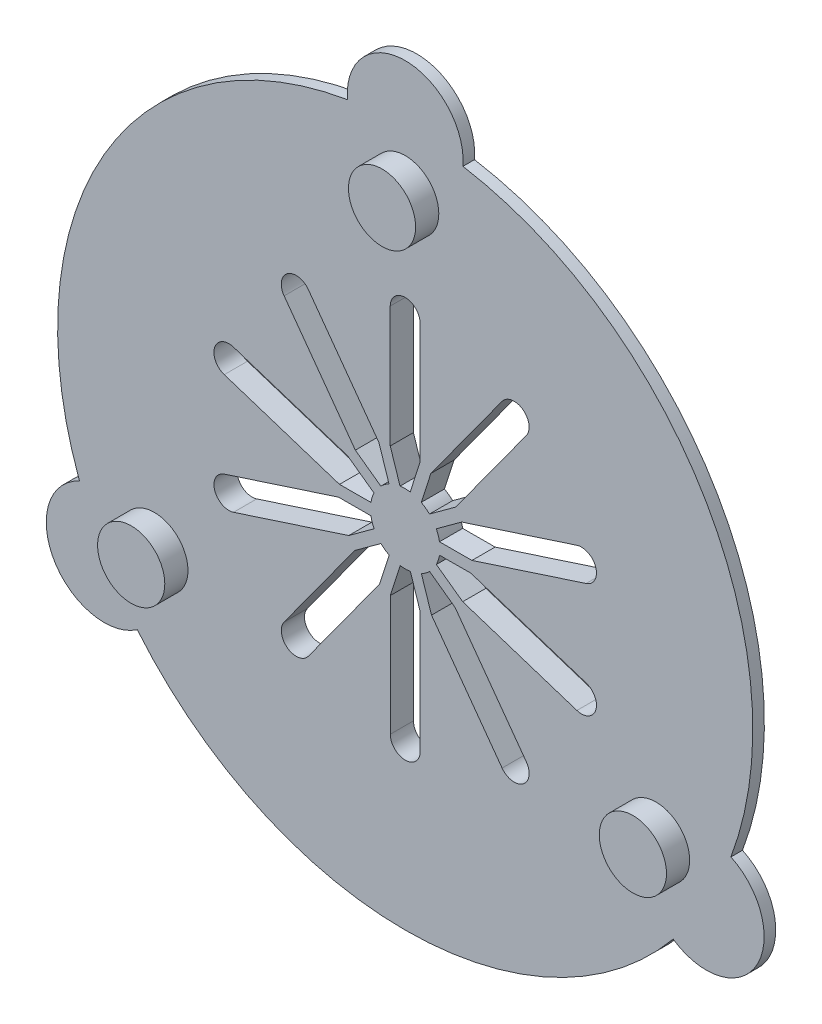
SolidWorks part; units mm, degrees
ref_plane "Спереди" through (0, 0, 0) normal (0, 0, 1) x (1, 0, 0)
ref_plane "Сверху" through (0, 0, 0) normal (0, 1, 0) x (1, 0, 0)
ref_plane "Справа" through (0, 0, 0) normal (1, 0, 0) x (0, 0, -1)
sketch "Sketch1" plane through (0, 0, 0) normal (0, 0, 1) x (1, 0, 0)
  line L0 (3.9, 6.755) -> (7.8, 0) construction
  line L2 (5.85, 10.1325) -> (11.7, 0) construction
  line L4 (7.8, 13.51) -> (15.6, 0) construction
  circle A61 centre (0, 0) radius 20
  circle A131 centre (0, 0) radius 1.25
  circle A484 centre (3.9, 0) radius 1.25
  circle A485 centre (7.8, 0) radius 1.25
  circle A486 centre (11.7, 0) radius 1.25
  circle A487 centre (15.6, 0) radius 1.25
  circle A488 centre (1.95, -3.3775) radius 1.25
  circle A489 centre (3.9, -6.755) radius 1.25
  circle A490 centre (5.85, -10.1325) radius 1.25
  circle A491 centre (7.8, -13.51) radius 1.25
  circle A492 centre (-1.95, -3.3775) radius 1.25
  circle A493 centre (-3.9, -6.755) radius 1.25
  circle A494 centre (-5.85, -10.1325) radius 1.25
  circle A495 centre (-7.8, -13.51) radius 1.25
  circle A496 centre (-3.9, 0) radius 1.25
  circle A497 centre (-7.8, 0) radius 1.25
  circle A498 centre (-11.7, 0) radius 1.25
  circle A499 centre (-15.6, 0) radius 1.25
  circle A500 centre (-1.95, 3.3775) radius 1.25
  circle A501 centre (-3.9, 6.755) radius 1.25
  circle A502 centre (-5.85, 10.1325) radius 1.25
  circle A503 centre (-7.8, 13.51) radius 1.25
  circle A504 centre (1.95, 3.3775) radius 1.25
  circle A505 centre (3.9, 6.755) radius 1.25
  circle A506 centre (5.85, 10.1325) radius 1.25
  circle A507 centre (7.8, 13.51) radius 1.25
  circle A508 centre (5.85, 3.3775) radius 1.25
  circle A509 centre (7.8, 6.755) radius 1.25
  circle A510 centre (9.75, 3.3775) radius 1.25
  circle A511 centre (11.7, 6.755) radius 1.25
  circle A512 centre (9.7491, 10.1341) radius 1.25
  circle A513 centre (13.6509, 3.3759) radius 1.25
  circle A514 centre (5.85, -3.3791) radius 1.25
  circle A515 centre (9.75, -3.3791) radius 1.25
  circle A516 centre (7.8, -6.7566) radius 1.25
  circle A517 centre (11.7, -6.7566) radius 1.25
  circle A518 centre (9.7491, -10.1356) radius 1.25
  circle A519 centre (13.6509, -3.3775) radius 1.25
  circle A520 centre (-0.0013, -6.7573) radius 1.25
  circle A521 centre (1.9487, -10.1348) radius 1.25
  circle A522 centre (-1.9513, -10.1348) radius 1.25
  circle A523 centre (-0.0013, -13.5123) radius 1.25
  circle A524 centre (-3.9032, -13.5123) radius 1.25
  circle A525 centre (3.9005, -13.5123) radius 1.25
  circle A526 centre (-5.8527, -3.3791) radius 1.25
  circle A527 centre (-7.8027, -6.7566) radius 1.25
  circle A528 centre (-9.7527, -3.3791) radius 1.25
  circle A529 centre (-11.7027, -6.7566) radius 1.25
  circle A530 centre (-13.6536, -3.3775) radius 1.25
  circle A531 centre (-9.7518, -10.1356) radius 1.25
  circle A532 centre (-5.8527, 3.3775) radius 1.25
  circle A533 centre (-9.7527, 3.3775) radius 1.25
  circle A534 centre (-7.8027, 6.755) radius 1.25
  circle A535 centre (-11.7027, 6.755) radius 1.25
  circle A536 centre (-9.7518, 10.1341) radius 1.25
  circle A537 centre (-13.6536, 3.3759) radius 1.25
  circle A538 centre (-0.0014, 6.7558) radius 1.25
  circle A539 centre (-1.9514, 10.1333) radius 1.25
  circle A540 centre (1.9486, 10.1333) radius 1.25
  circle A541 centre (-0.0014, 13.5108) radius 1.25
  circle A542 centre (3.9005, 13.5108) radius 1.25
  circle A543 centre (-3.9032, 13.5108) radius 1.25
  circle A544 centre (13.65, -1.1258) radius 2.2517 construction
  circle A545 centre (11.7009, -4.5044) radius 2.2522 construction
  circle A546 centre (9.75, -7.8834) radius 2.2522 construction
  circle A547 centre (7.7987, -11.2591) radius 2.2509 construction
  circle A548 centre (13.65, -1.1258) radius 0.65
  circle A549 centre (11.7009, -4.5044) radius 0.65
  circle A550 centre (9.75, -7.8834) radius 0.65
  circle A551 centre (7.7987, -11.2591) radius 0.65
  circle A552 centre (9.75, -1.1258) radius 0.65
  circle A553 centre (7.8009, -4.5044) radius 0.65
  circle A554 centre (5.85, -7.8834) radius 0.65
  circle A555 centre (3.8987, -11.2591) radius 0.65
  circle A556 centre (5.85, -1.1258) radius 0.65
  circle A557 centre (3.9009, -4.5044) radius 0.65
  circle A558 centre (1.95, -7.8834) radius 0.65
  circle A559 centre (-0.0013, -11.2591) radius 0.65
  circle A560 centre (1.95, -1.1258) radius 0.65
  circle A561 centre (0.0009, -4.5044) radius 0.65
  circle A562 centre (-1.95, -7.8834) radius 0.65
  circle A563 centre (-3.9013, -11.2591) radius 0.65
  circle A564 centre (-1.95, -1.1258) radius 0.65
  circle A565 centre (-3.8991, -4.5044) radius 0.65
  circle A566 centre (-5.85, -7.8834) radius 0.65
  circle A567 centre (-7.8013, -11.2591) radius 0.65
  circle A568 centre (-5.85, -1.1258) radius 0.65
  circle A569 centre (-7.7991, -4.5044) radius 0.65
  circle A570 centre (-9.75, -7.8834) radius 0.65
  circle A572 centre (-9.75, -1.1258) radius 0.65
  circle A573 centre (-11.6991, -4.5044) radius 0.65
  circle A576 centre (-13.65, -1.1258) radius 0.65
  circle A587 centre (0, 2.2517) radius 2.2517 construction
  circle A588 centre (0, 2.2517) radius 0.65
  circle A589 centre (3.9, 2.2517) radius 0.65
  circle A590 centre (7.8, 2.2517) radius 0.65
  circle A591 centre (11.7, 2.2517) radius 0.65
  circle A592 centre (15.6, 2.2517) radius 0.65
  circle A593 centre (1.9491, 5.6297) radius 2.2522 construction
  circle A594 centre (1.9491, 5.6297) radius 0.65
  circle A595 centre (5.8491, 5.6297) radius 0.65
  circle A596 centre (9.7491, 5.6297) radius 0.65
  circle A597 centre (13.6491, 5.6297) radius 0.65
  circle A598 centre (3.8991, 9.0072) radius 2.2522 construction
  circle A599 centre (3.8991, 9.0072) radius 0.65
  circle A600 centre (7.7991, 9.0072) radius 0.65
  circle A601 centre (11.6991, 9.0072) radius 0.65
  circle A602 centre (5.85, 12.3842) radius 2.2517 construction
  circle A603 centre (5.85, 12.3842) radius 0.65
  circle A604 centre (9.75, 12.3842) radius 0.65
  circle A605 centre (5.85, -14.6358) radius 0.65
  circle A606 centre (1.9509, -14.6353) radius 0.65
  circle A607 centre (-1.9491, -14.6353) radius 0.65
  circle A608 centre (-5.85, -14.6358) radius 0.65
  circle A609 centre (-15.6, 2.2517) radius 0.65
  circle A610 centre (-13.65, 5.6281) radius 0.65
  circle A611 centre (-11.7, 9.0056) radius 0.65
  circle A612 centre (-9.75, 12.3842) radius 0.65
  circle A613 centre (-5.85, 12.3842) radius 0.65
  circle A614 centre (-1.95, 12.3842) radius 0.65
  circle A615 centre (1.95, 12.3842) radius 0.65
  circle A616 centre (-7.8, 9.0056) radius 0.65
  circle A617 centre (-9.75, 5.6281) radius 0.65
  circle A618 centre (-11.7, 2.2517) radius 0.65
  circle A619 centre (-3.9, 9.0056) radius 0.65
  circle A620 centre (-5.85, 5.6281) radius 0.65
  circle A621 centre (-7.8, 2.2517) radius 0.65
  circle A622 centre (0, 9.0056) radius 0.65
  circle A623 centre (-1.95, 5.6281) radius 0.65
  circle A624 centre (-3.9, 2.2517) radius 0.65
  circle A625 centre (-15.5991, -4.5044) radius 0.65
  circle A626 centre (-13.65, -7.8834) radius 0.65
  circle A627 centre (-17.55, -7.8834) radius 0.65
  circle A628 centre (-19.5013, -11.2591) radius 0.65
  circle A629 centre (-15.6013, -11.2591) radius 0.65
  circle A630 centre (-11.7013, -11.2591) radius 0.65
  point P51 (0, 0)
  point P125 (-0.0013, -0.0008)
  point P231 (0, 0)
  dimension "D1" = 5
  dimension "D3" = 6
  dimension "D5" = 8
  dimension "D7" = 4
  dimension "D11" = 4
  dimension "D2" = 6
  dimension "D6" = 5
  dimension "D8" = 3
  dimension "D9" = 2
  dimension "D4" = 1.3
  dimension "D10" = 3
ref_plane "Plane1" through (0, 0, 10) normal (0, 0, 1) x (1, 0, 0)
sketch "Sketch2" plane through (0, 0, 10) normal (0, 0, 1) x (1, 0, 0)
  line L0 (-0.0032, 16) -> (0, 0) construction
  line L1 (1.2877, 16.0003) -> (1.2909, 0.0003)
  line L2 (-1.2941, 15.9997) -> (-1.2909, -0.0003)
  line L3 (8.3575, 13.7047) -> (-1.0445, 0.7585)
  line L4 (10.4465, 12.1876) -> (1.0445, -0.7585)
  line L5 (9.402, 12.9462) -> (0, 0) construction
  line L6 (14.8168, 6.1749) -> (-0.3991, 1.2276)
  line L7 (15.6151, 3.7197) -> (0.3991, -1.2276)
  line L8 (15.2159, 4.9473) -> (0, 0) construction
  line L9 (15.6165, -3.7135) -> (0.3987, 1.2278)
  line L10 (14.8192, -6.169) -> (-0.3987, -1.2278)
  line L11 (15.2179, -4.9412) -> (0, 0) construction
  line L12 (10.4513, -12.1834) -> (1.0442, 0.759)
  line L13 (8.363, -13.7014) -> (-1.0442, -0.759)
  line L14 (9.4072, -12.9424) -> (0, 0) construction
  line L15 (1.2941, -15.9997) -> (1.2909, 0.0003)
  line L16 (-1.2877, -16.0003) -> (-1.2909, -0.0003)
  line L17 (0.0032, -16) -> (0, 0) construction
  line L18 (-8.3575, -13.7047) -> (1.0445, -0.7585)
  line L19 (-10.4465, -12.1876) -> (-1.0445, 0.7585)
  line L20 (-9.402, -12.9462) -> (0, 0) construction
  line L21 (-14.8168, -6.1749) -> (0.3991, -1.2276)
  line L22 (-15.6151, -3.7197) -> (-0.3991, 1.2276)
  line L23 (-15.2159, -4.9473) -> (0, 0) construction
  line L24 (-15.6165, 3.7135) -> (-0.3987, -1.2278)
  line L25 (-14.8192, 6.169) -> (0.3987, 1.2278)
  line L26 (-15.2179, 4.9412) -> (0, 0) construction
  line L27 (-10.4513, 12.1834) -> (-1.0442, -0.759)
  line L28 (-8.363, 13.7014) -> (1.0442, 0.759)
  line L29 (-9.4072, 12.9424) -> (0, 0) construction
  circle A52 centre (0, 0) radius 16.85 construction
  circle A53 centre (0, 0) radius 18.85
  arc A54 (1.2877, 16.0003) -> (-1.2941, 15.9997) centre (-0.0032, 16) ccw
  arc A55 (-1.2909, -0.0003) -> (1.2909, 0.0003) centre (0, 0) ccw
  arc A56 (10.4465, 12.1876) -> (8.3575, 13.7047) centre (9.402, 12.9462) ccw
  arc A57 (-1.0445, 0.7585) -> (1.0445, -0.7585) centre (0, 0) ccw
  arc A58 (15.6151, 3.7197) -> (14.8168, 6.1749) centre (15.2159, 4.9473) ccw
  arc A59 (-0.3991, 1.2276) -> (0.3991, -1.2276) centre (0, 0) ccw
  arc A60 (14.8192, -6.169) -> (15.6165, -3.7135) centre (15.2179, -4.9412) ccw
  arc A61 (0.3987, 1.2278) -> (-0.3987, -1.2278) centre (0, 0) ccw
  arc A62 (8.363, -13.7014) -> (10.4513, -12.1834) centre (9.4072, -12.9424) ccw
  arc A63 (1.0442, 0.759) -> (-1.0442, -0.759) centre (0, 0) ccw
  arc A64 (-1.2877, -16.0003) -> (1.2941, -15.9997) centre (0.0032, -16) ccw
  arc A65 (1.2909, 0.0003) -> (-1.2909, -0.0003) centre (0, 0) ccw
  arc A66 (-10.4465, -12.1876) -> (-8.3575, -13.7047) centre (-9.402, -12.9462) ccw
  arc A67 (1.0445, -0.7585) -> (-1.0445, 0.7585) centre (0, 0) ccw
  arc A68 (-15.6151, -3.7197) -> (-14.8168, -6.1749) centre (-15.2159, -4.9473) ccw
  arc A69 (0.3991, -1.2276) -> (-0.3991, 1.2276) centre (0, 0) ccw
  arc A70 (-14.8192, 6.169) -> (-15.6165, 3.7135) centre (-15.2179, 4.9412) ccw
  arc A71 (-0.3987, -1.2278) -> (0.3987, 1.2278) centre (0, 0) ccw
  arc A72 (-8.363, 13.7014) -> (-10.4513, 12.1834) centre (-9.4072, 12.9424) ccw
  arc A73 (-1.0442, -0.759) -> (1.0442, 0.759) centre (0, 0) ccw
  point P1 (-0.0016, 8)
  point P9 (4.701, 6.4731)
  point P15 (7.608, 2.4737)
  point P21 (7.6089, -2.4706)
  point P27 (4.7036, -6.4712)
  point P33 (0.0016, -8)
  point P39 (-4.701, -6.4731)
  point P45 (-7.608, -2.4737)
  point P51 (-7.6089, 2.4706)
  point P57 (-4.7036, 6.4712)
  point P62 (0, 0)
extrude "Boss-Extrude1" add sketch "Sketch2" along normal blind 2 contours A53 A72 L28 L2 A54 L1 L3 A56 L4 L6 A58 L7 L9 A60 L10 L12 A62 L13 L15 A64 L16 L18 A66 L19 L21 A68 L22 L24 A70 L25 L27
sketch "Sketch3" plane through (0, 0, 12) normal (0, 0, 1) x (1, 0, 0)
  circle A0 centre (0, 0) radius 17.6
  circle A1 centre (0, 0) radius 30
  circle M33 centre (0, 0) radius 18.85
extrude "Boss-Extrude2" add sketch "Sketch3" against normal blind 1 contours A1 M33
sketch "Sketch4" plane through (0, 0, 12) normal (0, 0, 1) x (1, 0, 0)
  circle A0 centre (0, 0) radius 25 construction
  circle A1 centre (0, 25) radius 2.9
  circle A2 centre (21.6506, -12.5) radius 2.9
  circle A3 centre (-21.6506, -12.5) radius 2.9
  point P11 (0, 0)
  dimension "D1" = 3
extrude "Boss-Extrude3" add sketch "Sketch4" along normal blind 2
sketch "Sketch6" plane through (0, 0, 11) normal (0, 0, -1) x (-1, 0, 0)
  circle A0 centre (0, 30) radius 5
  circle A2 centre (25.9808, -15) radius 5
  circle A3 centre (-25.9808, -15) radius 5
  point P10 (0, 0)
  dimension "D1" = 3
extrude "Boss-Extrude4" add sketch "Sketch6" against normal blind 1
sketch "Sketch5" plane through (0, 0, 10) normal (0, 0, -1) x (-1, 0, 0)
  circle A0 centre (0, 25) radius 3
  circle A1 centre (21.6506, -12.5) radius 3
  circle A2 centre (-21.6506, -12.5) radius 3
sketch "Sketch9" plane through (0, 0, 0) normal (0, 0, 1) x (1, 0, 0)
  line L0 (-7.8, 13.51) -> (-7.8027, 6.755) construction
  line L1 (-9.7518, 10.1341) -> (-5.85, 10.1325) construction
  line L2 (-7.8008, 11.6325) -> (-7.8019, 8.6325) construction
  line L3 (-6.8008, 11.6321) -> (-6.8019, 8.6321)
  line L4 (-8.8008, 11.6329) -> (-8.8019, 8.6329)
  line L5 (-4.9008, 11.6329) -> (-4.9019, 8.6329)
  line L6 (-2.9008, 11.6321) -> (-2.9019, 8.6321)
  line L7 (-3.9008, 11.6325) -> (-3.9019, 8.6325) construction
  line L8 (-1.0008, 11.6329) -> (-1.0019, 8.6329)
  line L9 (0.9992, 11.6321) -> (0.9981, 8.6321)
  line L10 (-0.0008, 11.6325) -> (-0.0019, 8.6325) construction
  line L11 (2.8992, 11.6329) -> (2.8981, 8.6329)
  line L12 (4.8992, 11.6321) -> (4.8981, 8.6321)
  line L13 (3.8992, 11.6325) -> (3.8981, 8.6325) construction
  line L14 (6.7992, 11.6329) -> (6.7981, 8.6329)
  line L15 (8.7992, 11.6321) -> (8.7981, 8.6321)
  line L16 (7.7992, 11.6325) -> (7.7981, 8.6325) construction
  line L17 (-9.7518, 10.1341) -> (-9.7527, 3.3775) construction
  line L18 (-11.7027, 6.755) -> (-7.8027, 6.755) construction
  line L19 (-10.7035, 1.877) -> (-10.702, 4.877)
  line L22 (-9.7527, 3.3775) -> (-5.8527, 3.3775) construction
  line L25 (-7.8027, 6.755) -> (-7.8, 0) construction
  line L26 (-7.8035, 1.8775) -> (-7.8019, 4.8775) construction
  line L27 (-8.8035, 1.878) -> (-8.8019, 4.878)
  line L28 (-6.8035, 1.877) -> (-6.8019, 4.877)
  line L29 (-2.9035, 1.877) -> (-2.9019, 4.877)
  line L30 (-4.9035, 1.878) -> (-4.9019, 4.878)
  line L31 (-3.9035, 1.8775) -> (-3.9019, 4.8775) construction
  line L32 (0.9965, 1.877) -> (0.9981, 4.877)
  line L33 (-1.0035, 1.878) -> (-1.0019, 4.878)
  line L34 (-0.0035, 1.8775) -> (-0.0019, 4.8775) construction
  line L35 (4.8965, 1.877) -> (4.8981, 4.877)
  line L36 (2.8965, 1.878) -> (2.8981, 4.878)
  line L37 (3.8965, 1.8775) -> (3.8981, 4.8775) construction
  line L38 (8.7965, 1.877) -> (8.7981, 4.877)
  line L39 (6.7965, 1.878) -> (6.7981, 4.878)
  line L40 (7.7965, 1.8775) -> (7.7981, 4.8775) construction
  line L41 (12.6965, 1.877) -> (12.6981, 4.877)
  line L42 (10.6965, 1.878) -> (10.6981, 4.878)
  line L43 (11.6965, 1.8775) -> (11.6981, 4.8775) construction
  line L44 (-12.7035, 1.878) -> (-12.7019, 4.878)
  line L45 (-11.7035, 1.8775) -> (-11.702, 4.8775) construction
  line L46 (-9.7527, -3.3791) -> (-5.8527, -3.3791) construction
  line L47 (-7.8, 0) -> (-7.8027, -6.7566) construction
  line L48 (-7.8046, -4.8791) -> (-7.8008, -1.8791) construction
  line L49 (-8.8046, -4.8778) -> (-8.8008, -1.8778)
  line L50 (-6.8046, -4.8804) -> (-6.8008, -1.8804)
  line L51 (-2.9046, -4.8804) -> (-2.9008, -1.8804)
  line L52 (-4.9046, -4.8778) -> (-4.9008, -1.8778)
  line L53 (-3.9046, -4.8791) -> (-3.9008, -1.8791) construction
  line L54 (0.9954, -4.8804) -> (0.9992, -1.8804)
  line L55 (-1.0046, -4.8778) -> (-1.0008, -1.8778)
  line L56 (-0.0046, -4.8791) -> (-0.0008, -1.8791) construction
  line L57 (4.8954, -4.8804) -> (4.8992, -1.8804)
  line L58 (2.8954, -4.8778) -> (2.8992, -1.8778)
  line L59 (3.8954, -4.8791) -> (3.8992, -1.8791) construction
  line L60 (8.7954, -4.8804) -> (8.7992, -1.8804)
  line L61 (6.7954, -4.8778) -> (6.7992, -1.8778)
  line L62 (7.7954, -4.8791) -> (7.7992, -1.8791) construction
  line L63 (12.6954, -4.8804) -> (12.6992, -1.8804)
  line L64 (10.6954, -4.8778) -> (10.6992, -1.8778)
  line L65 (11.6954, -4.8791) -> (11.6992, -1.8791) construction
  line L66 (-10.7046, -4.8804) -> (-10.7008, -1.8804)
  line L67 (-12.7046, -4.8778) -> (-12.7008, -1.8778)
  line L68 (-11.7046, -4.8791) -> (-11.7008, -1.8791) construction
  line L69 (-9.7518, -10.1356) -> (-5.482, -10.1356) construction
  line L70 (-7.8027, -6.7566) -> (-7.8, -13.51) construction
  line L71 (-7.8007, -8.6356) -> (-7.8007, -11.6356) construction
  line L72 (-6.8007, -8.6356) -> (-6.8007, -11.6356)
  line L73 (-8.8007, -8.6356) -> (-8.8007, -11.6356)
  line L74 (-4.9007, -8.6356) -> (-4.9007, -11.6356)
  line L75 (-2.9007, -8.6356) -> (-2.9007, -11.6356)
  line L76 (-3.9007, -8.6356) -> (-3.9007, -11.6356) construction
  line L77 (-1.0007, -8.6356) -> (-1.0007, -11.6356)
  line L78 (0.9993, -8.6356) -> (0.9993, -11.6356)
  line L79 (-0.0007, -8.6356) -> (-0.0007, -11.6356) construction
  line L80 (2.8993, -8.6356) -> (2.8993, -11.6356)
  line L81 (4.8993, -8.6356) -> (4.8993, -11.6356)
  line L82 (3.8993, -8.6356) -> (3.8993, -11.6356) construction
  line L83 (6.7993, -8.6356) -> (6.7993, -11.6356)
  line L84 (8.7993, -8.6356) -> (8.7993, -11.6356)
  line L85 (7.7993, -8.6356) -> (7.7993, -11.6356) construction
  arc A0 (-6.8008, 11.6321) -> (-8.8008, 11.6329) centre (-7.8008, 11.6325) ccw
  arc A1 (-8.8019, 8.6329) -> (-6.8019, 8.6321) centre (-7.8019, 8.6325) ccw
  arc A2 (-2.9008, 11.6321) -> (-4.9008, 11.6329) centre (-3.9008, 11.6325) ccw
  arc A3 (-4.9019, 8.6329) -> (-2.9019, 8.6321) centre (-3.9019, 8.6325) ccw
  arc A4 (0.9992, 11.6321) -> (-1.0008, 11.6329) centre (-0.0008, 11.6325) ccw
  arc A5 (-1.0019, 8.6329) -> (0.9981, 8.6321) centre (-0.0019, 8.6325) ccw
  arc A6 (4.8992, 11.6321) -> (2.8992, 11.6329) centre (3.8992, 11.6325) ccw
  arc A7 (2.8981, 8.6329) -> (4.8981, 8.6321) centre (3.8981, 8.6325) ccw
  arc A8 (8.7992, 11.6321) -> (6.7992, 11.6329) centre (7.7992, 11.6325) ccw
  arc A9 (6.7981, 8.6329) -> (8.7981, 8.6321) centre (7.7981, 8.6325) ccw
  arc A14 (-8.8035, 1.878) -> (-6.8035, 1.877) centre (-7.8035, 1.8775) ccw
  arc A15 (-6.8019, 4.877) -> (-8.8019, 4.878) centre (-7.8019, 4.8775) ccw
  arc A16 (-4.9035, 1.878) -> (-2.9035, 1.877) centre (-3.9035, 1.8775) ccw
  arc A17 (-2.9019, 4.877) -> (-4.9019, 4.878) centre (-3.9019, 4.8775) ccw
  arc A18 (-1.0035, 1.878) -> (0.9965, 1.877) centre (-0.0035, 1.8775) ccw
  arc A19 (0.9981, 4.877) -> (-1.0019, 4.878) centre (-0.0019, 4.8775) ccw
  arc A20 (2.8965, 1.878) -> (4.8965, 1.877) centre (3.8965, 1.8775) ccw
  arc A21 (4.8981, 4.877) -> (2.8981, 4.878) centre (3.8981, 4.8775) ccw
  arc A22 (6.7965, 1.878) -> (8.7965, 1.877) centre (7.7965, 1.8775) ccw
  arc A23 (8.7981, 4.877) -> (6.7981, 4.878) centre (7.7981, 4.8775) ccw
  arc A24 (10.6965, 1.878) -> (12.6965, 1.877) centre (11.6965, 1.8775) ccw
  arc A25 (12.6981, 4.877) -> (10.6981, 4.878) centre (11.6981, 4.8775) ccw
  arc A26 (-12.7035, 1.878) -> (-10.7035, 1.877) centre (-11.7035, 1.8775) ccw
  arc A27 (-10.702, 4.877) -> (-12.7019, 4.878) centre (-11.702, 4.8775) ccw
  arc A28 (-8.8046, -4.8778) -> (-6.8046, -4.8804) centre (-7.8046, -4.8791) ccw
  arc A29 (-6.8008, -1.8804) -> (-8.8008, -1.8778) centre (-7.8008, -1.8791) ccw
  arc A30 (-4.9046, -4.8778) -> (-2.9046, -4.8804) centre (-3.9046, -4.8791) ccw
  arc A31 (-2.9008, -1.8804) -> (-4.9008, -1.8778) centre (-3.9008, -1.8791) ccw
  arc A32 (-1.0046, -4.8778) -> (0.9954, -4.8804) centre (-0.0046, -4.8791) ccw
  arc A33 (0.9992, -1.8804) -> (-1.0008, -1.8778) centre (-0.0008, -1.8791) ccw
  arc A34 (2.8954, -4.8778) -> (4.8954, -4.8804) centre (3.8954, -4.8791) ccw
  arc A35 (4.8992, -1.8804) -> (2.8992, -1.8778) centre (3.8992, -1.8791) ccw
  arc A36 (6.7954, -4.8778) -> (8.7954, -4.8804) centre (7.7954, -4.8791) ccw
  arc A37 (8.7992, -1.8804) -> (6.7992, -1.8778) centre (7.7992, -1.8791) ccw
  arc A38 (10.6954, -4.8778) -> (12.6954, -4.8804) centre (11.6954, -4.8791) ccw
  arc A39 (12.6992, -1.8804) -> (10.6992, -1.8778) centre (11.6992, -1.8791) ccw
  arc A40 (-12.7046, -4.8778) -> (-10.7046, -4.8804) centre (-11.7046, -4.8791) ccw
  arc A41 (-10.7008, -1.8804) -> (-12.7008, -1.8778) centre (-11.7008, -1.8791) ccw
  arc A42 (-6.8007, -8.6356) -> (-8.8007, -8.6356) centre (-7.8007, -8.6356) ccw
  arc A43 (-8.8007, -11.6356) -> (-6.8007, -11.6356) centre (-7.8007, -11.6356) ccw
  arc A44 (-2.9007, -8.6356) -> (-4.9007, -8.6356) centre (-3.9007, -8.6356) ccw
  arc A45 (-4.9007, -11.6356) -> (-2.9007, -11.6356) centre (-3.9007, -11.6356) ccw
  arc A46 (0.9993, -8.6356) -> (-1.0007, -8.6356) centre (-0.0007, -8.6356) ccw
  arc A47 (-1.0007, -11.6356) -> (0.9993, -11.6356) centre (-0.0007, -11.6356) ccw
  arc A48 (4.8993, -8.6356) -> (2.8993, -8.6356) centre (3.8993, -8.6356) ccw
  arc A49 (2.8993, -11.6356) -> (4.8993, -11.6356) centre (3.8993, -11.6356) ccw
  arc A50 (8.7993, -8.6356) -> (6.7993, -8.6356) centre (7.7993, -8.6356) ccw
  arc A51 (6.7993, -11.6356) -> (8.7993, -11.6356) centre (7.7993, -11.6356) ccw
  circle A52 centre (0, 0) radius 16.85 construction
  circle A53 centre (0, 0) radius 18.85
  point P10 (-7.8014, 10.1325)
  point P18 (-3.9014, 10.1325)
  point P25 (-0.0014, 10.1325)
  point P32 (3.8986, 10.1325)
  point P39 (7.7986, 10.1325)
  point P50 (-11.7027, 3.3775)
  point P58 (-7.8027, 3.3775)
  point P68 (-3.9027, 3.3775)
  point P75 (-0.0027, 3.3775)
  point P82 (3.8973, 3.3775)
  point P89 (7.7973, 3.3775)
  point P96 (11.6973, 3.3775)
  point P108 (-7.8027, -3.3791)
  point P116 (-3.9027, -3.3791)
  point P123 (-0.0027, -3.3791)
  point P130 (3.8973, -3.3791)
  point P137 (7.7973, -3.3791)
  point P144 (11.6973, -3.3791)
  point P151 (-11.7027, -3.3791)
  point P162 (-7.8007, -10.1356)
  point P170 (-3.9007, -10.1356)
  point P177 (-0.0007, -10.1356)
  point P184 (3.8993, -10.1356)
  point P191 (7.7993, -10.1356)
  dimension "D1" = 2
  dimension "D15" = 2
  dimension "D2" = 3
  dimension "D4" = 2
  dimension "D5" = 3
  dimension "D6" = 2
  dimension "D7" = 3
  dimension "D9" = 2
  dimension "D12" = 3
  dimension "D13" = 2
  dimension "D3" = 5
  dimension "D8" = 6
  dimension "D10" = 6
  dimension "D11" = 2
  dimension "D14" = 5
sketch "Sketch10" plane through (0, 0, 20) normal (0, 0, 1) x (1, 0, 0)
  line L1 (-9.8683, 13.2069) -> (9.8683, 13.2069)
  line L2 (-9.8683, 13.2069) -> (-9.8683, -13.2069)
  line L3 (-9.8683, -13.2069) -> (9.8683, -13.2069)
  line L4 (9.8683, 13.2069) -> (9.8683, -13.2069)
  line L5 (-9.8683, 13.2069) -> (9.8683, -13.2069) construction
  line L6 (-9.8683, -13.2069) -> (9.8683, 13.2069) construction
  line L7 (-14.0535, 6.7065) -> (14.0535, 6.7065)
  line L8 (-14.0535, 6.7065) -> (-14.0535, -6.7065)
  line L9 (-14.0535, -6.7065) -> (14.0535, -6.7065)
  line L10 (14.0535, 6.7065) -> (14.0535, -6.7065)
  line L11 (-14.0535, 6.7065) -> (14.0535, -6.7065) construction
  line L12 (-14.0535, -6.7065) -> (14.0535, 6.7065) construction
  circle A0 centre (0, 0) radius 21.6778
  point P0 (0, 0)
  point P6 (0, 0)
fillet "Fillet1" [suppressed] radius 0.5
sketch "Sketch12" plane through (0, 0, 10) normal (0, 0, -1) x (-1, 0, 0)
  line L0 (-1.9972, -6.0904) -> (1.9972, 6.0904) construction
  line L3 (-2.4723, -5.9346) -> (1.5221, 6.2462)
  line L4 (-1.5221, -6.2462) -> (2.4723, 5.9346)
  line L5 (-6.4109, -0.4826) -> (6.4082, -0.5174)
  line L6 (-6.4082, 0.5174) -> (6.4109, 0.4826)
  line L7 (-6.4095, 0.0174) -> (6.4095, -0.0174) construction
  line L8 (-2.44, 5.948) -> (1.4881, -6.2544)
  line L9 (-1.4881, 6.2544) -> (2.44, -5.948)
  line L10 (-1.9641, 6.1012) -> (1.9641, -6.1012) construction
  line L11 (4.9029, 4.1586) -> (-5.4885, -3.348)
  line L12 (5.4885, 3.348) -> (-4.9029, -4.1586)
  line L13 (5.1957, 3.7533) -> (-5.1957, -3.7533) construction
  line L14 (5.4702, -3.3778) -> (-4.8802, 4.1852)
  line L15 (4.8802, -4.1852) -> (-5.4702, 3.3778)
  line L16 (5.1752, -3.7815) -> (-5.1752, 3.7815) construction
  circle A2 centre (0, 0) radius 3
  arc A3 (-2.4723, -5.9346) -> (-1.5221, -6.2462) centre (-1.9972, -6.0904) ccw
  arc A4 (2.4723, 5.9346) -> (1.5221, 6.2462) centre (1.9972, 6.0904) ccw
  arc A5 (-6.4082, 0.5174) -> (-6.4109, -0.4826) centre (-6.4095, 0.0174) ccw
  arc A6 (6.4082, -0.5174) -> (6.4109, 0.4826) centre (6.4095, -0.0174) ccw
  arc A7 (-1.4881, 6.2544) -> (-2.44, 5.948) centre (-1.9641, 6.1012) ccw
  arc A8 (1.4881, -6.2544) -> (2.44, -5.948) centre (1.9641, -6.1012) ccw
  arc A9 (5.4885, 3.348) -> (4.9029, 4.1586) centre (5.1957, 3.7533) ccw
  arc A10 (-5.4885, -3.348) -> (-4.9029, -4.1586) centre (-5.1957, -3.7533) ccw
  arc A11 (4.8802, -4.1852) -> (5.4702, -3.3778) centre (5.1752, -3.7815) ccw
  arc A12 (-4.8802, 4.1852) -> (-5.4702, 3.3778) centre (-5.1752, 3.7815) ccw
  point P5 (0, 0)
  point P15 (0, 0)
  point P22 (0, 0)
  point P29 (0, 0)
  point P36 (0, 0)
  point P41 (0, 0)
  line M7 (10.4513, 12.1834) -> (3.38, 2.4547)
  line M8 (3.38, 2.4547) -> (14.8192, 6.169)
  line M10 (15.6165, 3.7135) -> (4.1773, -0.0008)
  line M11 (4.1773, -0.0008) -> (15.6151, -3.7197)
  line M13 (14.8168, -6.1749) -> (3.379, -2.456)
  line M14 (3.379, -2.456) -> (10.4465, -12.1876)
  line M16 (8.3575, -13.7047) -> (1.2901, -3.9731)
  line M17 (1.2901, -3.9731) -> (1.2877, -16.0003)
  line M19 (-1.2941, -15.9997) -> (-1.2917, -3.9726)
  line M20 (-1.2917, -3.9726) -> (-8.363, -13.7014)
  line M22 (-10.4513, -12.1834) -> (-3.38, -2.4547)
  line M23 (-3.38, -2.4547) -> (-14.8192, -6.169)
  line M25 (-15.6165, -3.7135) -> (-4.1773, 0.0008)
  line M26 (-4.1773, 0.0008) -> (-15.6151, 3.7197)
  line M28 (-14.8168, 6.1749) -> (-3.379, 2.456)
  line M29 (-3.379, 2.456) -> (-10.4465, 12.1876)
  line M31 (-8.3575, 13.7047) -> (-1.2901, 3.9731)
  line M32 (-1.2901, 3.9731) -> (-1.2877, 16.0003)
  line M34 (1.2941, 15.9997) -> (1.2917, 3.9726)
  line M35 (1.2917, 3.9726) -> (8.363, 13.7014)
  dimension "D1" = 1
extrude "Boss-Extrude5" add sketch "Sketch12" against normal blind 2 contours A2 L9 L8 M32 M31 | A2 L4 L3 M35 M34 | A2 L12 L11 M8 M7 | A2 L5 L6 M11 M10 | A2 L15 L14 M14 M13 | A2 L8 L9 M17 M16 | A2 L3 L4 M20 M19 | A2 L11 L12 M23 M22 | A2 L6 L5 M26 M25 | A2 L14 L15 M29 M28
sketch "Sketch13" plane through (0, 0, 10) normal (0, 0, -1) x (-1, 0, 0)
  circle A0 centre (0, 0) radius 3
extrude "Boss-Extrude6" add sketch "Sketch13" against normal blind 2
